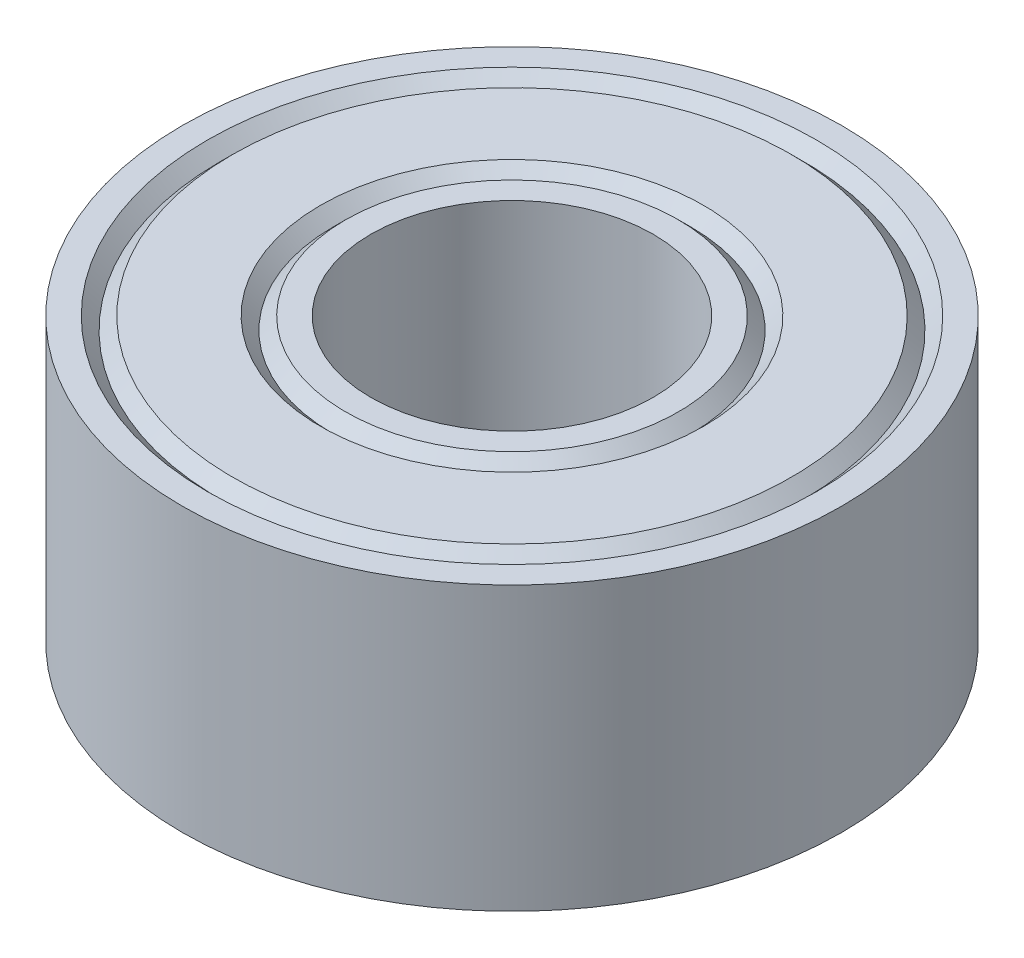
SolidWorks part; units mm, degrees
ref_plane "Front Plane" through (0, 0, 0) normal (0, 0, 1) x (1, 0, 0)
ref_plane "Top Plane" through (0, 0, 0) normal (0, 1, 0) x (1, 0, 0)
ref_plane "Right Plane" through (0, 0, 0) normal (1, 0, 0) x (0, 0, -1)
sketch "Sketch1" plane through (0, 0, 0) normal (0, 0, 1) x (1, 0, 0)
  line L0 (0, 1.5) -> (0, -1.5) construction
  line L1 (-1.5, 1.5) -> (-1.7667, 1.5)
  line L2 (-1.5, 1.5) -> (-1.5, -1.5)
  line L3 (-1.5, -1.5) -> (-1.7667, -1.5)
  line L4 (-3.5, 1.5) -> (-3.5, -1.5)
  line L5 (-3.2333, 1.5) -> (-3.1, 1.3667)
  line L6 (-3.1, 1.3667) -> (-2.9667, 1.5)
  line L7 (-2.0333, 1.5) -> (-1.9, 1.3667)
  line L8 (-1.9, 1.3667) -> (-1.7667, 1.5)
  line L9 (-3.2333, -1.5) -> (-3.1, -1.3667)
  line L10 (-3.1, -1.3667) -> (-2.9667, -1.5)
  line L11 (-2.0333, -1.5) -> (-1.9, -1.3667)
  line L12 (-1.9, -1.3667) -> (-1.7667, -1.5)
  line L13 (-2.0333, -1.5) -> (-2.9667, -1.5)
  line L14 (-3.2333, -1.5) -> (-3.5, -1.5)
  line L15 (-3.2333, 1.5) -> (-3.5, 1.5)
  line L16 (-2.0333, 1.5) -> (-2.9667, 1.5)
  line L17 (-3.1, 1.3667) -> (-1.9, 1.3667) construction
  line L18 (-3.1, 1.3667) -> (-3.1, -1.3667) construction
  line L19 (-1.9, -1.3667) -> (-3.1, -1.3667) construction
  line L20 (-1.9, 1.3667) -> (-1.9, -1.3667) construction
  line L21 (-3.1, 0) -> (-2.7, 0) construction
  line L22 (-1.7667, 1.5) -> (-2.0333, 1.5) construction
  line L23 (-2.7, 0) -> (-2.3, 0) construction
  line L24 (-3.1, 0) -> (-3.5, 0) construction
  line L25 (-2.3, 0) -> (-1.9, 0) construction
  line L26 (-1.9, 0) -> (-1.5, 0) construction
  dimension "D1" = 3
  dimension "D2" = 3
  dimension "D3" = 7
revolve "Revolve1" add sketch "Sketch1" angle 360 about L0
